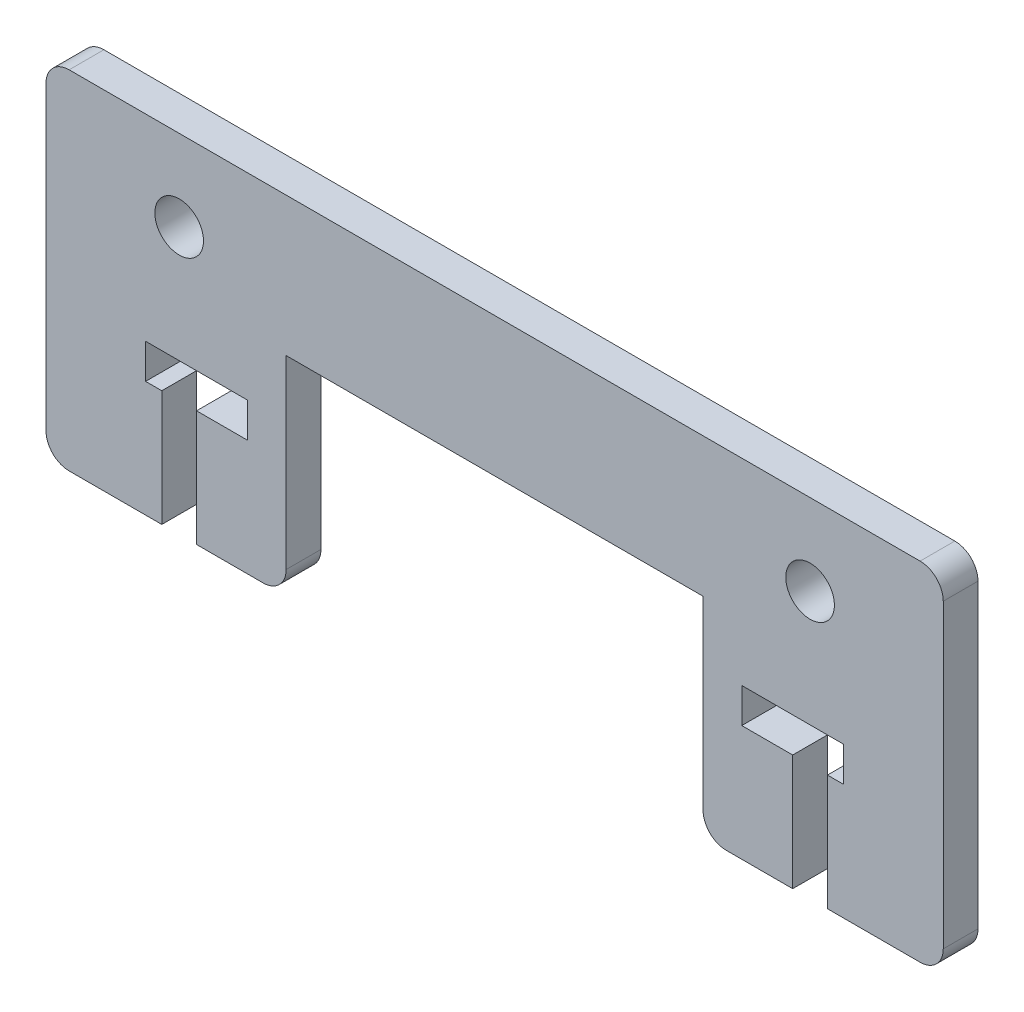
SolidWorks part; units mm, degrees
material "Zoltek Panex 33"
ref_plane "前视基准面" through (0, 0, 0) normal (0, 0, 1) x (1, 0, 0)
ref_plane "上视基准面" through (0, 0, 0) normal (0, 1, 0) x (1, 0, 0)
ref_plane "右视基准面" through (0, 0, 0) normal (1, 0, 0) x (0, 0, -1)
sketch "草图1" plane through (0, 0, 0) normal (0, 0, 1) x (1, 0, 0)
  line L1 (23.32, 41.9586) -> (27.19, 41.9586)
  line L2 (1.45, 41.9586) -> (5.32, 41.9586)
  line L5 (-0.05, 46.9586) -> (-0.05, 41.9586)
  line L6 (-0.05, 41.9586) -> (1.45, 41.9586) construction
  line L7 (-0.05, 41.9586) -> (-5.05, 41.9586)
  line L8 (-5.05, 41.9586) -> (-5.05, 56.9586)
  line L9 (-5.05, 56.9586) -> (14.32, 56.9586)
  line L10 (33.69, 56.9586) -> (33.69, 41.9586)
  line L11 (33.69, 41.9586) -> (28.69, 41.9586)
  line L14 (27.94, 53.4586) -> (0.7, 53.4586) construction
  line L15 (14.32, 53.4586) -> (14.32, 56.9586) construction
  line L19 (14.32, 56.9586) -> (33.69, 56.9586)
  line L31 (14.32, 41.9586) -> (14.32, 53.4586) construction
  line L33 (1.45, 41.9586) -> (1.45, 46.9586)
  line L34 (1.45, 46.9586) -> (3.65, 46.9586)
  line L35 (3.65, 46.9586) -> (3.65, 48.4586)
  line L36 (3.65, 48.4586) -> (-0.75, 48.4586)
  line L37 (-0.75, 48.4586) -> (-0.75, 46.9586)
  line L38 (-0.75, 46.9586) -> (-0.05, 46.9586)
  line L39 (0.7, 41.9586) -> (0.7, 56.9586) construction
  line L40 (27.19, 41.9586) -> (27.19, 46.9586)
  line L41 (28.69, 46.9586) -> (28.69, 41.9586)
  line L42 (29.39, 46.9586) -> (28.69, 46.9586)
  line L43 (29.39, 48.4586) -> (29.39, 46.9586)
  line L44 (24.99, 48.4586) -> (29.39, 48.4586)
  line L45 (24.99, 46.9586) -> (24.99, 48.4586)
  line L46 (27.19, 46.9586) -> (24.99, 46.9586)
  line L47 (5.32, 41.9586) -> (5.32, 50.9586)
  line L48 (5.32, 50.9586) -> (23.32, 50.9586)
  line L49 (23.32, 41.9586) -> (23.32, 50.9586)
  line L50 (5.32, 41.9586) -> (23.32, 50.9586) construction
  line L51 (5.32, 50.9586) -> (23.32, 41.9586) construction
  circle A0 centre (27.94, 53.4586) radius 1.05
  circle A1 centre (0.7, 53.4586) radius 1.05
  point P2 (14.32, 46.4586)
  dimension "D8" = 2.1
  dimension "D2" = 1.5
  dimension "D3" = 25.74
  dimension "D4" = 5
  dimension "D5" = 5
  dimension "D6" = 15
  dimension "D7" = 2.2
  dimension "D9" = 9
  dimension "D10" = 18
  dimension "D11" = 3.5
  dimension "D12" = 2.2
  dimension "D13" = 1.5
  dimension "D14" = 5
extrude "凸台-拉伸1" add sketch "草图1" along normal blind 1.5
fillet "圆角1" radius 1 6 edges at (33.69, 41.9586, 0.75) (33.69, 56.9586, 0.75) (-5.05, 41.9586, 0.75) (-5.05, 56.9586, 0.75) (23.32, 41.9586, 0.75) (5.32, 41.9586, 0.75)
